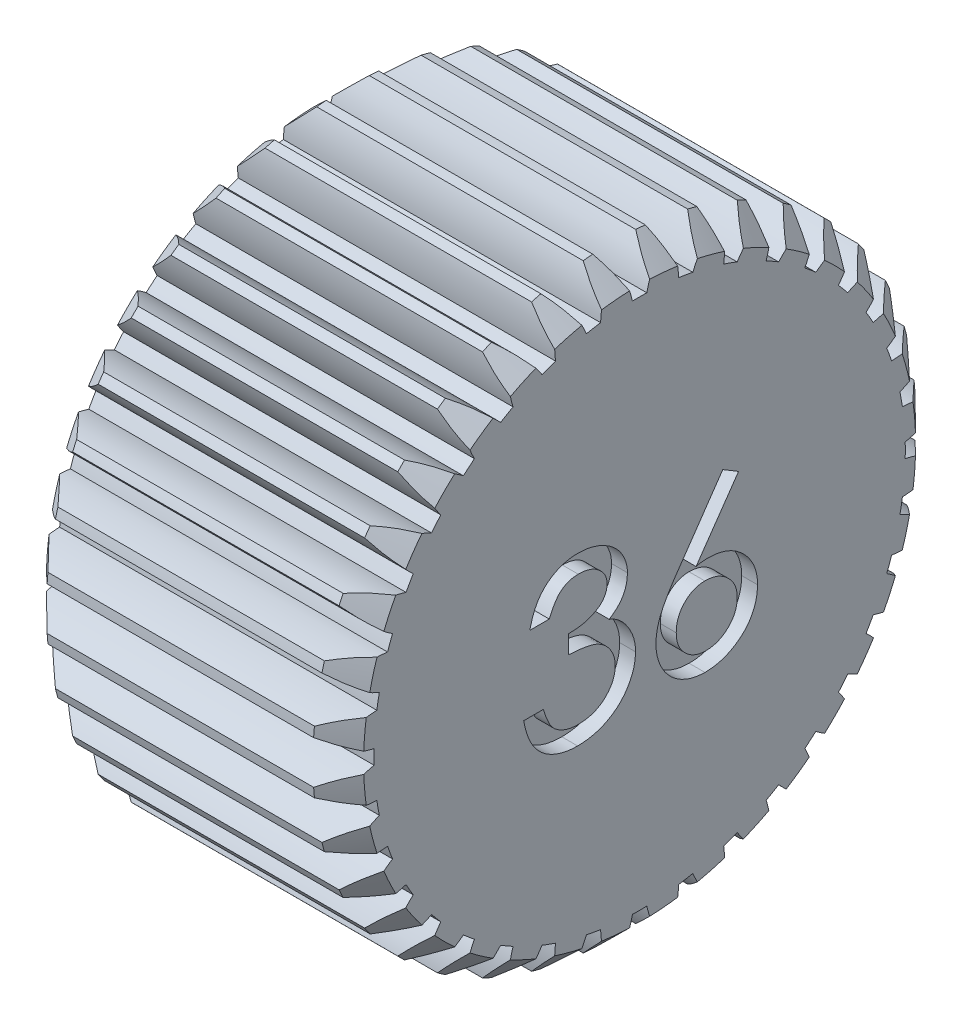
SolidWorks part; units mm, degrees
ref_plane "Plane1" through (0, 0, 0) normal (0, 0, 1) x (1, 0, 0)
ref_plane "Plane2" through (0, 0, 0) normal (0, 1, 0) x (1, 0, 0)
ref_plane "Plane3" through (0, 0, 0) normal (1, 0, 0) x (0, 0, -1)
sketch "HoldingSke" plane through (0, 0, 0) normal (0, 1, 0) x (1, 0, 0)
  line L0 (0, 0) -> (1.618, -1.1756)
  line L1 (-15, 0) -> (100, 0) construction
  line L2 (0, 0) -> (-2.1039, 2.3779)
  line L3 (0, 0) -> (-11.863, 4.5341)
  line L4 (0, 0) -> (6.9867, 5.0761)
  line L5 (0, 0) -> (-46.8476, -17.4728)
  line L6 (0, 0) -> (-8.2896, -5.593)
  line L7 (-2.1039, 2.3779) -> (8.6586, 51.2059)
  line L8 (-76.2, 54.61) -> (-75.3, 54.61)
  line L9 (-71.009, 38.7566) -> (-53.1078, 45.2721)
  line L10 (-76.2, 71.12) -> (104.1128, 71.12)
  line L11 (0, 0) -> (-10, 0)
  line L12 (-76.2, 101.6) -> (-76.181, 101.6)
  line L13 (24.9733, 27.94) -> (52.9518, 28.4284)
  line L14 (24.9733, 27.94) -> (24.9743, 27.94)
  line L15 (24.9733, 27.94) -> (100.4006, 29.5858)
  line L16 (-63.627, -0.5) -> (-12.827, -0.5)
  circle A0 centre (0, 0) radius 2.5
  circle A1 centre (0, 0) radius 8.374
  circle A2 centre (0, 0) radius 37.5
  circle A3 centre (0, 0) radius 2.5
sketch "BasProSke" plane through (0, 0, 0) normal (0, 1, 0) x (1, 0, 0)
  line L0 (-10, 0) -> (60, 0) construction
  line L1 (0, 0) -> (0, 9.5)
  line L2 (0, 0) -> (10, 0)
  line L3 (10, 0) -> (10, 9.5)
  line L4 (10, 9.5) -> (0, 9.5)
revolve "Base-Revolve" add sketch "BasProSke" angle 360 about L0
sketch "TooCutSke" plane through (0, 0, 0) normal (1, 0, 0) x (0, 0, -1)
  line L1 (0, 0) -> (0, 107) construction
  line L2 (0, 0) -> (-0.4258, 8.9899) construction
  line L3 (0, 0) -> (-1.5676, 17.9172) construction
  line L4 (-0.4258, 8.9899) -> (-0.7838, 8.9586) construction
  arc A0 (0.2272, 8.3709) -> (-0.2272, 8.3709) centre (0, 0) ccw
  arc A1 (0.6921, 9.5002) -> (-0.6921, 9.5002) centre (0, 0) ccw
  circle A2 centre (0, 0) radius 9 construction
  circle A3 centre (0, 0) radius 8.4572 construction
  arc A4 (-0.2272, 8.3709) -> (-0.6921, 9.5002) centre (-3.7404, 7.5851) ccw
  arc A5 (0.6921, 9.5002) -> (0.2272, 8.3709) centre (3.7404, 7.5851) ccw
extrude "ToothCut" cut sketch "TooCutSke" along normal through all
fillet "Breaks" [suppressed] radius 0.01
fillet "RootFillets" [suppressed] radius 0.126
pattern_circular "TeethCuts" count 36 every 10 about axis through (-10, 0, 0) along (1, 0, 0) of "ToothCut", "RootFillets", "Breaks"
sketch "HubNeaOneSke" plane through (0, 0, 0) normal (-1, 0, 0) x (0, 0, 1)
  circle A0 centre (0, 0) radius 8.374
extrude "HubNearOne" [suppressed] add sketch "HubNeaOneSke" along normal blind 40.0001
sketch "HubNeaBotSke" plane through (0, 0, 0) normal (-1, 0, 0) x (0, 0, 1)
  circle A0 centre (0, 0) radius 8.374
extrude "HubNearBoth" [suppressed] add sketch "HubNeaBotSke" along normal blind 20
ref_plane "FarPln" through (10, 0, 0) normal (1, 0, 0) x (0, 0, -1)
sketch "HubFarSke" plane through (10, 0, 0) normal (1, 0, 0) x (0, 0, -1)
  circle A0 centre (0, 0) radius 8.374
extrude "HubFar" [suppressed] add sketch "HubFarSke" along normal blind 20
sketch "BorSke" plane through (0, 0, 0) normal (1, 0, 0) x (0, 0, -1)
  circle A0 centre (0, 0) radius 2.5
extrude "Bore" cut sketch "BorSke" along normal mid plane 1
sketch "KeySke" plane through (0, 0, 0) normal (1, 0, 0) x (0, 0, -1)
  line L0 (-1, 0) -> (-1, 3.4)
  line L1 (-1, 3.4) -> (1, 3.4)
  line L2 (1, 3.4) -> (1, 0)
  line L3 (0, 0) -> (0, 34) construction
  line L4 (-1, 0) -> (1, 0)
extrude "Keyway" [suppressed] cut sketch "KeySke" along normal mid plane 100.0001
pattern_circular "Keyway2" [suppressed] count 2 every 90 about axis through (-10, 0, 0) along (1, 0, 0)
sketch "Sketch1" [suppressed] plane through (10, 0, 0) normal (1, 0, 0) x (0, 0, -1)
  circle A0 centre (0, 0) radius 2.5 construction
  circle A1 centre (0, 0) radius 2.5
extrude "Boss-Extrude1" [suppressed] add sketch "Sketch1" against normal up to surface (10 mm away)
sketch "Sketch2" plane through (0, 0, 0) normal (0, 1, 0) x (1, 0, 0)
  line L0 (0, 0) -> (-6.253, 0) construction
  line L1 (0, 0.2272) -> (0, -0.2272) construction
  line L2 (0, 9.5) -> (0, 8.7)
  line L3 (0, 8.7) -> (0.8, 9.5)
  line L4 (0.8, 9.5) -> (0, 9.5)
  line L5 (0, 8.5448) -> (0, 7.363) construction
  line L6 (5, 9.4494) -> (5, 13.3549) construction
  line L7 (10, 9.4494) -> (0, 9.4494) construction
  line L8 (9.2, 9.5) -> (10, 9.5)
  line L9 (10, 8.7) -> (9.2, 9.5)
  line L10 (10, 9.5) -> (10, 8.7)
  dimension "D1" = 0.8
  dimension "D2" = 19
revolve "Cut-Revolve1" cut sketch "Sketch2" angle 360 about L0
sketch "Sketch3" plane through (10, 0, 0) normal (1, 0, 0) x (0, 0, -1)
  line L0 (-6.7702, -2.7811) -> (6.7702, -2.7811) construction
  text T0 "<b>36</b>\r\n" font "Century Gothic" height 5
  point P2 (0, -2.7811)
extrude "Cut-Extrude1" cut sketch "Sketch3" against normal blind 0.5
equation "' \"Module@HoldingSke\" = 6.35"
equation "' \"Num_teeth@HoldingSke\" = 12"
equation "' \"Ap@HoldingSke\" =  20"
equation "' \"Ap@HoldingSke\" = 20"
equation "' \"Width@HoldingSke\" = 0.5 * 25.4"
equation "' \"Hub_dia@HoldingSke\"= 1 * 25.4"
equation "' \"Hub_dia@HoldingSke\" = 1 * 25.4"
equation "' \"Overall_len@HoldingSke\" = 1.0 * 25.4"
equation "' \"Bore@HoldingSke\" = 0.75 * 25.4"
equation "' \"T_dim@HoldingSke\" = 0.1 * 25.4"
equation "' \"Width@KeySke\" = 0.25 * 25.4"
equation "' \"Show_teeth@HoldingSke\" = 13"
equation "' \"Backlash@HoldingSke\" = 0.009 * 25.4"
equation "' \"Addendum_fac@HoldingSke\" = 1.0"
equation "' \"Dedendum_fac@HoldingSke\" = 1.25"
equation "' \"Dedendum_add@HoldingSke\" = 0.00005 * 25.4"
equation "' \"Clearance_fac@HoldingSke\" = 0.25"
equation "\"Pitch@HoldingSke\" = 1 / \"Module@HoldingSke\""
equation "\"Overcut_dia@TooCutSke\" = (\"Num_teeth@HoldingSke\" + 2 * \"Addendum_fac@HoldingSke\") / \"Pitch@HoldingSke\" + 0.002 * 25.4"
equation "\"Pitch_dia@TooCutSke\" = \"Num_teeth@HoldingSke\" / \"Pitch@HoldingSke\""
equation "\"Base_dia@TooCutSke\" = \"Num_teeth@HoldingSke\" / \"Pitch@HoldingSke\" * cos((\"Ap@HoldingSke\"  * 3.14159265 / 180))"
equation "\"Root_dia@TooCutSke\" = (\"Num_teeth@HoldingSke\" + 2) / \"Pitch@HoldingSke\" - 2 * (\"Addendum_fac@HoldingSke\" + \"Dedendum_fac@HoldingSke\") / \"Pitch@HoldingSke\" - \"Dedendum_add@HoldingSke\" * 2"
equation "\"Half_ang@TooCutSke\" = 180 / \"Num_teeth@HoldingSke\""
equation "\"Half_CT@TooCutSke\" = \"Num_teeth@HoldingSke\" / \"Pitch@HoldingSke\" * sin((3.14159265 / 2 / \"Num_teeth@HoldingSke\")) / 2 - 7 * \"Backlash@HoldingSke\" / 4"
equation "\"Flank_rad@TooCutSke\" = \"Num_teeth@HoldingSke\" / \"Pitch@HoldingSke\" / 5"
equation "\"Radius@RootFillets\" = \"Clearance_fac@HoldingSke\" / \"Pitch@HoldingSke\" + \"Dedendum_add@HoldingSke\""
equation "\"Break_rad@Breaks\" = 0.02 / \"Pitch@HoldingSke\""
equation "\"Thickness@HoldingSke\" = \"Width@HoldingSke\""
equation "\"OAL@HoldingSke\" = \"Thickness@HoldingSke\""
equation "\"MHD@HoldingSke\" = (\"Num_teeth@HoldingSke\" + 2) / \"Pitch@HoldingSke\" - 2 * (\"Addendum_fac@HoldingSke\" + \"Dedendum_fac@HoldingSke\")  / \"Pitch@HoldingSke\" - \"Dedendum_add@HoldingSke\" * 2"
equation "\"MBD@HoldingSke\" = (\"Num_teeth@HoldingSke\" + 2) / \"Pitch@HoldingSke\" - 2 * (\"Addendum_fac@HoldingSke\" + \"Dedendum_fac@HoldingSke\")  / \"Pitch@HoldingSke\" - \"Dedendum_add@HoldingSke\" * 2 - 0.002 * 25.4"
equation "\"MHD@HoldingSke\" = ((sgn( \"MHD@HoldingSke\" - \"Hub_dia@HoldingSke\" )-1)*( \"MHD@HoldingSke\" - \"Hub_dia@HoldingSke\" ))/-2+ \"Hub_dia@HoldingSke\""
equation "\"MBD@HoldingSke\" = ((sgn( \"MBD@HoldingSke\" - \"Bore@HoldingSke\" )-1)*( \"MBD@HoldingSke\" - \"Bore@HoldingSke\" ))/-2+ \"Bore@HoldingSke\""
equation "\"OAL@HoldingSke\" = ((sgn( \"OAL@HoldingSke\" - \"Overall_len@HoldingSke\" )+1)*( \"OAL@HoldingSke\" - \"Overall_len@HoldingSke\" ))/2 + \"Overall_len@HoldingSke\" + 0.000002 * 25.4"
equation "\"Num_teeth@TeethCuts\" = int( \"Show_teeth@HoldingSke\" ) + 1"
equation "\"Num_teeth@TeethCuts\" = ((sgn( \"Num_teeth@TeethCuts\" - \"Num_teeth@HoldingSke\" )-1)*( \"Num_teeth@TeethCuts\" - \"Num_teeth@HoldingSke\" ))/-2+ \"Num_teeth@HoldingSke\""
equation "\"Num_teeth@TeethCuts\" = ((sgn( \"Num_teeth@TeethCuts\" - 2.0)+1)*( \"Num_teeth@TeethCuts\" - 2.0))/2 +2.0"
equation "\"Angle@TeethCuts\" = 360.0 / \"Num_teeth@HoldingSke\""
equation "\"Diameter@BasProSke\" = (\"Num_teeth@HoldingSke\" + 2 * \"Addendum_fac@HoldingSke\") / \"Pitch@HoldingSke\""
equation "\"Thickness@BasProSke\"  = \"Thickness@HoldingSke\""
equation "' \"Fillet_rad@BasProSke\" =  \"Thickness@HoldingSke\" * 0.05"
equation "' \"Fillet_rad@BasProSke\" = \"Thickness@HoldingSke\" * 0.05"
equation "\"MHD@HoldingSke\" = ((sgn( \"MHD@HoldingSke\" - \"Root_dia@TooCutSke\" )-1)*( \"MHD@HoldingSke\" - \"Root_dia@TooCutSke\" ))/-2+ \"Root_dia@TooCutSke\""
equation "\"Diameter@HubNeaOneSke\" = \"MHD@HoldingSke\""
equation "\"Length@HubNearOne\" = \"OAL@HoldingSke\" - \"Thickness@BasProSke\""
equation "\"Diameter@HubNeaBotSke\" = \"MHD@HoldingSke\""
equation "\"Length@HubNearBoth\" = ( \"OAL@HoldingSke\" - \"Thickness@BasProSke\" ) / 2.0"
equation "\"Thickness@FarPln\" = \"Thickness@BasProSke\""
equation "\"Diameter@HubFarSke\" = \"MHD@HoldingSke\""
equation "\"Length@HubFar\" = ( \"OAL@HoldingSke\" - \"Thickness@BasProSke\" ) / 2.0"
equation "\"D1@Keyway\" = \"OAL@HoldingSke\" * 2.0"
equation "\"Offset@KeySke\" = \"T_dim@HoldingSke\" + \"MBD@HoldingSke\" / 2.0"
